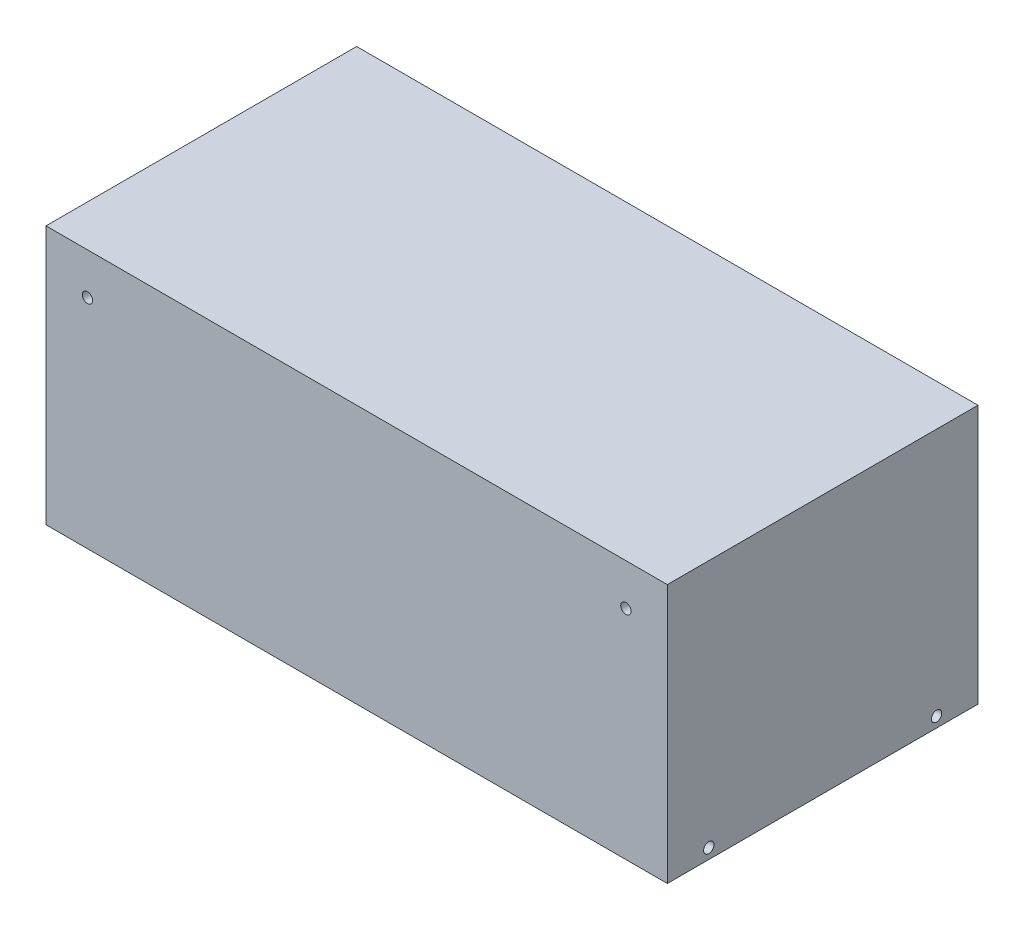
SolidWorks part; units mm, degrees
material "ABS PC"
ref_plane "Front Plane" through (0, 0, 0) normal (0, 0, 1) x (1, 0, 0)
ref_plane "Top Plane" through (0, 0, 0) normal (0, 1, 0) x (1, 0, 0)
ref_plane "Right Plane" through (0, 0, 0) normal (1, 0, 0) x (0, 0, -1)
sketch "Sketch1" plane through (0, 0, 0) normal (0, 1, 0) x (1, 0, 0)
  line L1 (150, -75) -> (-150, -75)
  line L2 (150, -75) -> (150, 75)
  line L3 (150, 75) -> (-150, 75)
  line L4 (-150, -75) -> (-150, 75)
  line L5 (150, -75) -> (-150, 75) construction
  line L6 (150, 75) -> (-150, -75) construction
  point P0 (0, 0)
  dimension "D1" = 300
  dimension "D2" = 150
extrude "Boss-Extrude1" add sketch "Sketch1" along normal blind 125
sketch "Sketch2" plane through (0, 0, 0) normal (0, -1, 0) x (1, 0, 0)
  line L0 (-150, 75) -> (150, 75) construction
  line L1 (135, -60) -> (-135, -60)
  line L2 (135, -60) -> (135, 60)
  line L3 (135, 60) -> (-135, 60)
  line L4 (-135, -60) -> (-135, 60)
  line L5 (135, -60) -> (-135, 60) construction
  line L6 (135, 60) -> (-135, -60) construction
  line L7 (150, 75) -> (150, -75) construction
  point P0 (0, 0)
  point P8 (150, 0)
  dimension "D1" = 15
  dimension "D2" = 15
extrude "Cut-Extrude1" cut sketch "Sketch2" against normal blind 110
sketch "Sketch4" plane through (150, 0, 0) normal (1, 0, 0) x (0, 0, -1)
  line L0 (-75, 0) -> (75, 0) construction
  line L1 (75, 125) -> (75, 0) construction
  line L5 (-75, 125) -> (-75, 0) construction
  circle A0 centre (-55, 5) radius 2.5
  circle A1 centre (55, 5) radius 2.5
  dimension "D3" = 5
  dimension "D4" = 5
  dimension "D1" = 5
  dimension "D2" = 20
  dimension "D5" = 5
  dimension "D6" = 20
extrude "Cut-Extrude5" cut sketch "Sketch4" against normal blind 350
sketch "Sketch6" plane through (0, 0, 75) normal (0, 0, 1) x (1, 0, 0)
  line L0 (-150, 125) -> (-150, 0) construction
  line L1 (-150, 125) -> (150, 125) construction
  line L2 (0, 140.9499) -> (0, -14.4188) construction
  circle A0 centre (-130, 105) radius 2.5
  circle A1 centre (130, 105) radius 2.5
  dimension "D1" = 5
  dimension "D2" = 20
  dimension "D3" = 20
extrude "Cut-Extrude6" cut sketch "Sketch6" against normal blind 175
